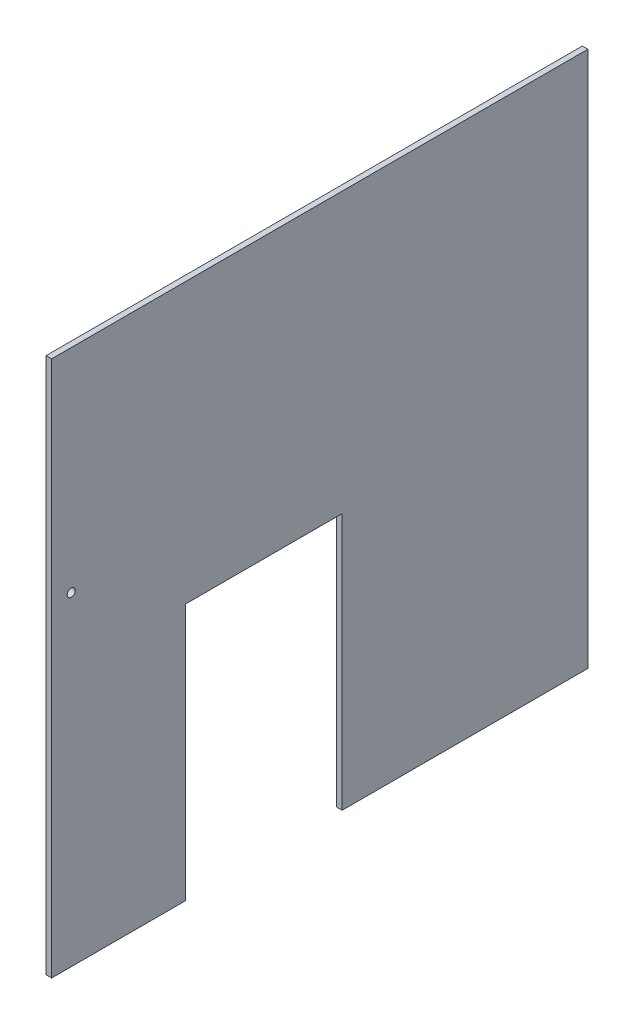
SolidWorks part; units mm, degrees
ref_plane "Front Plane" through (0, 0, 0) normal (0, 0, 1) x (1, 0, 0)
ref_plane "Top Plane" through (0, 0, 0) normal (0, 1, 0) x (1, 0, 0)
ref_plane "Right Plane" through (0, 0, 0) normal (1, 0, 0) x (0, 0, -1)
sketch "Sketch1" plane through (0, 0, 0) normal (1, 0, 0) x (0, 0, -1)
  line L1 (-152.4, 152.4) -> (152.4, 152.4)
  line L2 (-152.4, 152.4) -> (-152.4, -152.4)
  line L3 (-152.4, -152.4) -> (152.4, -152.4)
  line L4 (152.4, 152.4) -> (152.4, -152.4)
  line L5 (-152.4, 152.4) -> (152.4, -152.4) construction
  line L6 (-152.4, -152.4) -> (152.4, 152.4) construction
  line L7 (-76.2, -152.4) -> (12.7, -152.4)
  line L8 (-76.2, -152.4) -> (-76.2, -6.35)
  line L9 (-76.2, -6.35) -> (12.7, -6.35)
  line L10 (12.7, -152.4) -> (12.7, -6.35)
  point P0 (0, 0)
  dimension "D1" = 304.8
  dimension "D2" = 304.8
  dimension "D3" = 76.2
  dimension "D4" = 88.9
  dimension "D5" = 146.05
extrude "Boss-Extrude1" add sketch "Sketch1" along normal blind 3.175 contours L10 L3 L4 L1 L2 L8 L9
sketch "Sketch2" plane through (3.175, 0, 0) normal (1, 0, 0) x (0, 0, -1)
  line L0 (-152.4, 152.4) -> (-152.4, -152.4) construction
  line L1 (-152.4, -152.4) -> (-76.2, -152.4) construction
  circle A0 centre (-141.2875, 31.75) radius 2.286
  dimension "D2" = 4.572
  dimension "D1" = 11.1125
  dimension "D3" = 184.15
extrude "Cut-Extrude1" cut sketch "Sketch2" against normal through all
